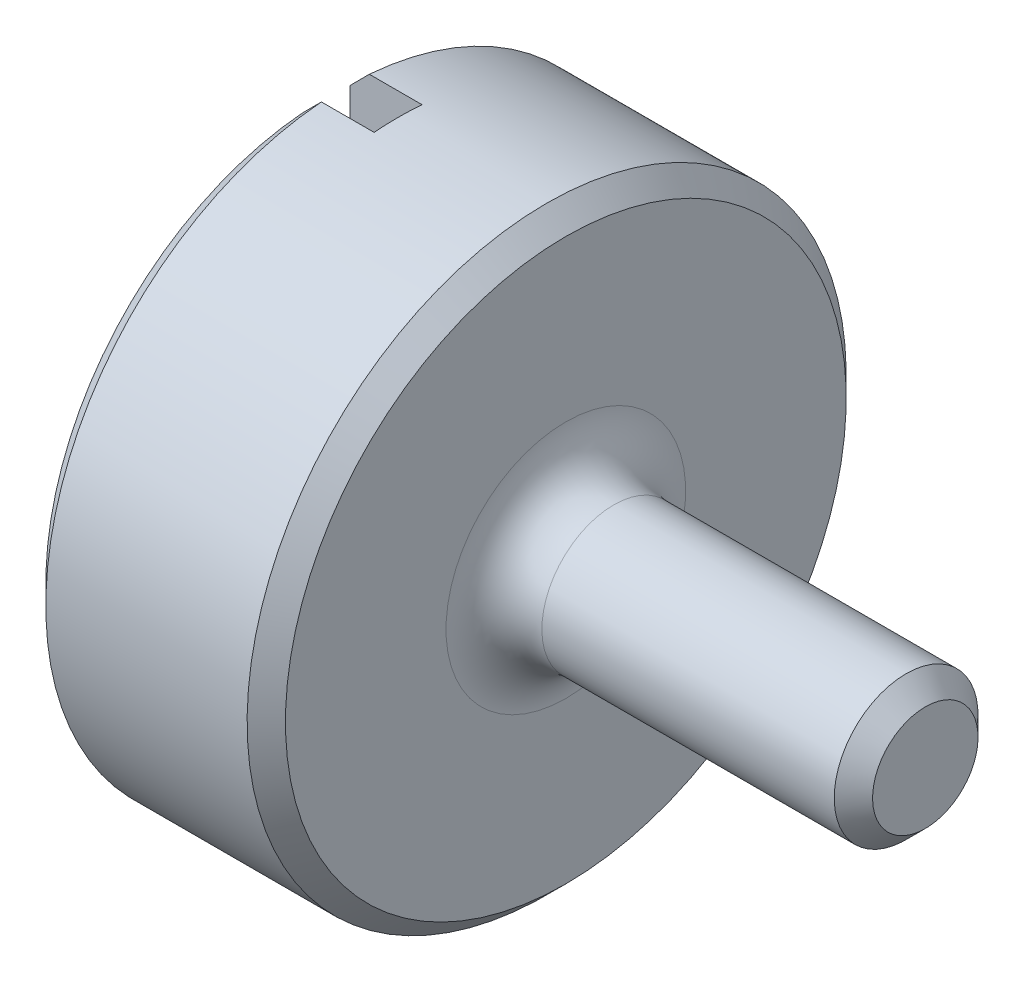
SolidWorks part; units mm, degrees
material "Liga 1060"
ref_plane "Plano frontal" through (0, 0, 0) normal (0, 0, 1) x (1, 0, 0)
ref_plane "Plano superior" through (0, 0, 0) normal (0, 1, 0) x (1, 0, 0)
ref_plane "Plano direito" through (0, 0, 0) normal (1, 0, 0) x (0, 0, -1)
sketch "Esboço1" plane through (0, 0, 0) normal (0, 0, 1) x (1, 0, 0)
  line L0 (0, 0) -> (0, 12.5)
  line L1 (0, 12.5) -> (10, 12.5)
  line L2 (10, 12.5) -> (10, 3)
  line L3 (10, 3) -> (25, 3)
  line L4 (25, 3) -> (25, 0)
  line L5 (25, 0) -> (0, 0) construction
  line L6 (0, 0) -> (25, 0)
  dimension "D1" = 6
  dimension "D2" = 25
  dimension "D3" = 15
  dimension "D4" = 10
revolve "Revolução1" add sketch "Esboço1" angle 360 about L5
cosmetic thread "Representação de rosca2" parameters "D1"=12, "D2"=4.891
chamfer "Chanfro1" distance 0.8 angle 45 3 edges at (0, 12.5, 0) (10, 12.5, 0) (25, 3, 0)
fillet "Filete1" radius 2 1 edges at (10, 3, 0)
sketch "Esboço2" plane through (0, 0, 0) normal (-1, 0, 0) x (0, 0, 1)
  line L1 (-1, -15) -> (1, -15)
  line L2 (-1, -15) -> (-1, 15)
  line L3 (-1, 15) -> (1, 15)
  line L4 (1, -15) -> (1, 15)
  line L5 (-1, -15) -> (1, 15) construction
  line L6 (-1, 15) -> (1, -15) construction
  point P0 (0, 0)
  dimension "D1" = 2
  dimension "D2" = 30
extrude "Corte-extrusão1" cut sketch "Esboço2" against normal blind 3
